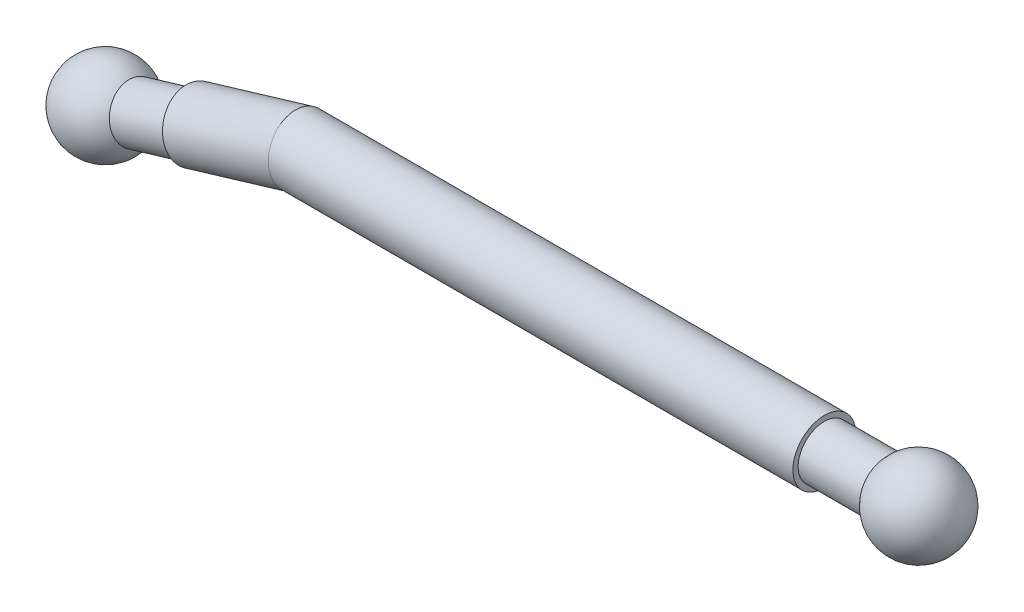
SolidWorks part; units mm, degrees
ref_plane "Front Plane" through (0, 0, 0) normal (0, 0, 1) x (1, 0, 0)
ref_plane "Top Plane" through (0, 0, 0) normal (0, 1, 0) x (1, 0, 0)
ref_plane "Right Plane" through (0, 0, 0) normal (1, 0, 0) x (0, 0, -1)
sketch "Sketch1" plane through (0, 0, 0) normal (1, 0, 0) x (0, 0, -1)
  circle A0 centre (0, 0) radius 3
  dimension "D1" = 6
sketch "Sketch2" plane through (0, 0, 0) normal (0, 0, 1) x (1, 0, 0)
  line L0 (0, 0) -> (-50, 0)
  line L1 (-50, 0) -> (-60, 0) construction
  line L2 (-60, 0) -> (-60, -3) construction
  line L3 (-50, 0) -> (-60, -3)
  dimension "D1" = 50
  dimension "D2" = 10
  dimension "D3" = 3
sweep "Sweep2" add profiles "Sketch1" path "Sketch2"
sketch "Sketch3" plane through (-55.8716, -16.7615, 0) normal (-0.9578, -0.2873, 0) x (0, 0, 1)
  circle A0 centre (0, 14.2332) radius 2.5
  dimension "D1" = 5
extrude "Boss-Extrude1" add sketch "Sketch3" along normal blind 6
ref_plane "Plane1" through (-64.492, -19.3476, 0) normal (-0.9578, -0.2873, 0) x (0, 0, 1)
sketch "Sketch4" plane through (-64.492, -19.3476, 0) normal (-0.9578, -0.2873, 0) x (0, 0, 1)
  line L0 (0, 18.2332) -> (0, 10.2332) construction
  line L1 (0, 18.2332) -> (0, 10.2332)
  arc A0 (0, 18.2332) -> (0, 10.2332) centre (0, 14.2332) cw
  point P5 (0, 14.2332)
  dimension "D2" = 8
revolve "Revolve1" add sketch "Sketch4" angle 360 about L0
sketch "Sketch5" plane through (0, 0, 0) normal (1, 0, 0) x (0, 0, -1)
  circle A0 centre (0, 0) radius 2.5
  dimension "D1" = 5
extrude "Boss-Extrude2" add sketch "Sketch5" along normal blind 6
ref_plane "Plane2" through (9, 0, 0) normal (1, 0, 0) x (0, 0, -1)
sketch "Sketch6" plane through (9, 0, 0) normal (1, 0, 0) x (0, 0, -1)
  line L0 (0, 4) -> (0, -4)
  arc A0 (0, 4) -> (0, -4) centre (0, 0) cw
  point P5 (0, 0)
  dimension "D2" = 8
revolve "Revolve2" add sketch "Sketch6" angle 360 about L0
